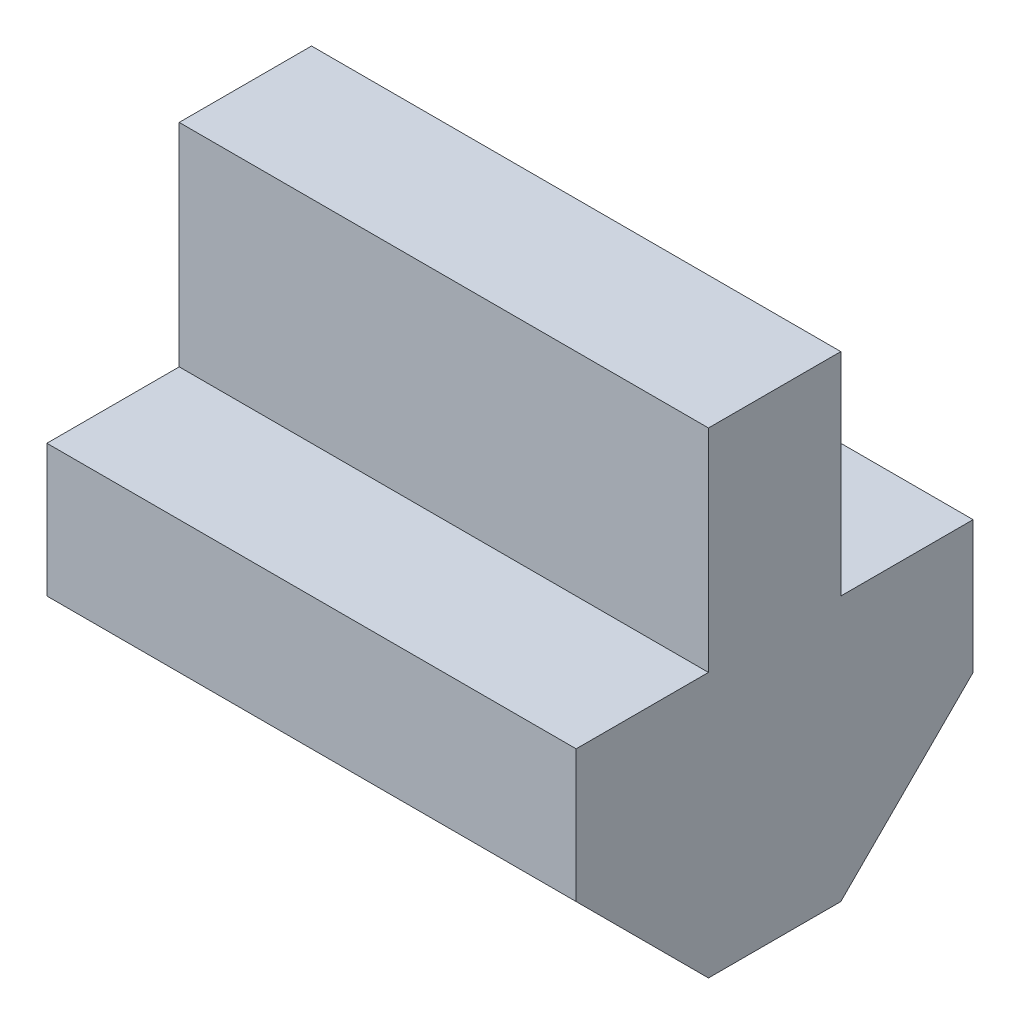
SolidWorks part; units mm, degrees
material "PP Kopolimer"
ref_plane "Front Plane" through (0, 0, 0) normal (0, 0, 1) x (1, 0, 0)
ref_plane "Top Plane" through (0, 0, 0) normal (0, 1, 0) x (1, 0, 0)
ref_plane "Right Plane" through (0, 0, 0) normal (1, 0, 0) x (0, 0, -1)
sketch "Szkic1" plane through (0, 0, 0) normal (0, 1, 0) x (1, 0, 0)
  line L1 (-2, -1.5) -> (2, -1.5)
  line L2 (-2, -1.5) -> (-2, 1.5)
  line L3 (-2, 1.5) -> (2, 1.5)
  line L4 (2, -1.5) -> (2, 1.5)
  line L5 (-2, -1.5) -> (2, 1.5) construction
  line L6 (-2, 1.5) -> (2, -1.5) construction
  point P0 (0, 0)
  dimension "D1" = 3
  dimension "D2" = 4
extrude "Dodanie-wyciągnięcie1" add sketch "Szkic1" along normal blind 2 contours L3 L4 L1 L2
sketch "Szkic3" plane through (0, 2, 0) normal (0, 1, 0) x (1, 0, 0)
  line L0 (2, -1.5) -> (2, 1.5) construction
  line L1 (-2, -0.5) -> (2, -0.5)
  line L2 (-2, -0.5) -> (-2, 0.5)
  line L3 (-2, 0.5) -> (2, 0.5)
  line L4 (2, -0.5) -> (2, 0.5)
  line L5 (-2, -0.5) -> (2, 0.5) construction
  line L6 (-2, 0.5) -> (2, -0.5) construction
  point P0 (0, 0)
extrude "Dodanie-wyciągnięcie2" add sketch "Szkic3" along normal blind 1.6
chamfer "Sfazowanie1" distance 1 angle 45 1 edges at (0, 0, 1.5)
chamfer "Sfazowanie2" distance 1 angle 45 1 edges at (0, 0, -1.5)
